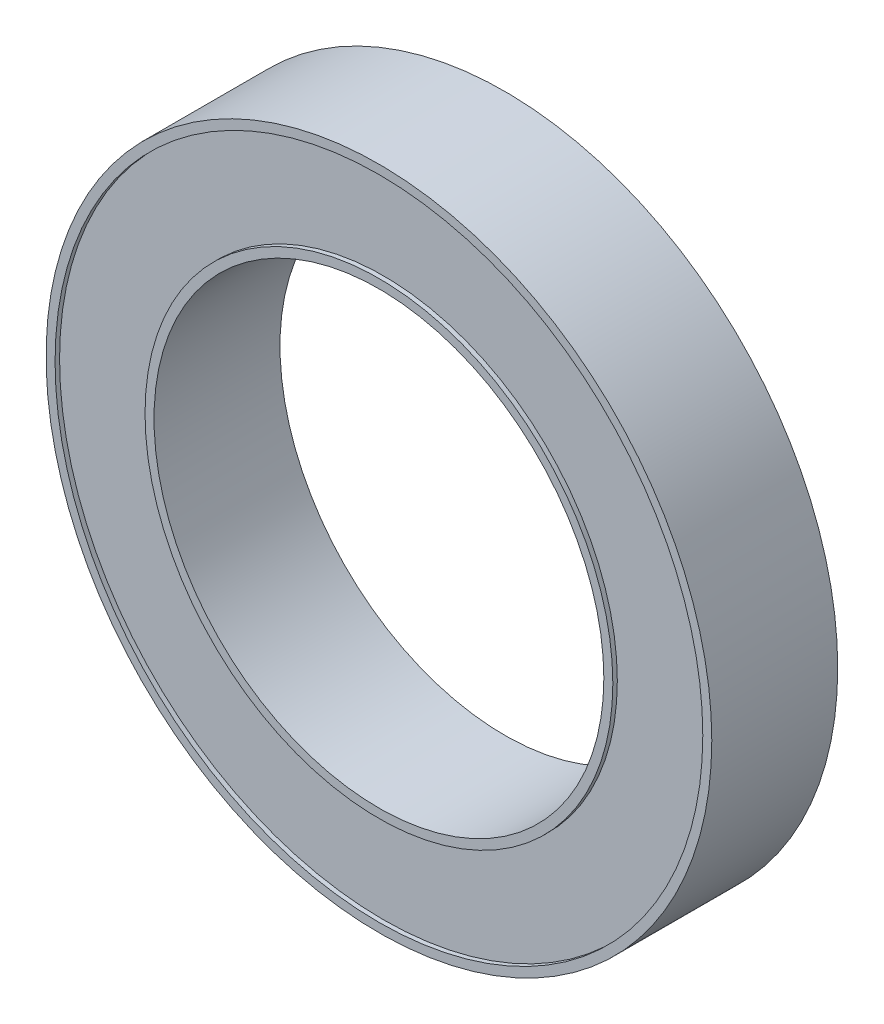
SolidWorks part; units mm, degrees
ref_plane "Front Plane" through (0, 0, 0) normal (0, 0, 1) x (1, 0, 0)
ref_plane "Top Plane" through (0, 0, 0) normal (0, 1, 0) x (1, 0, 0)
ref_plane "Right Plane" through (0, 0, 0) normal (1, 0, 0) x (0, 0, -1)
sketch "Sketch1" plane through (0, 0, 0) normal (0, 0, 1) x (1, 0, 0)
  circle A0 centre (0, 0) radius 12.5
  circle A1 centre (0, 0) radius 18.5
  dimension "D1" = 37
  dimension "D2" = 25
extrude "Boss-Extrude1" add sketch "Sketch1" along normal mid plane 7
sketch "Sketch2" plane through (0, 0, 3.5) normal (0, 0, 1) x (1, 0, 0)
  circle A2 centre (0, 0) radius 18
  circle A3 centre (0, 0) radius 18
  circle A5 centre (0, 0) radius 13
  circle A6 centre (0, 0) radius 13
  dimension "D1" = 0.5
  dimension "D2" = 0.5
extrude "Cut-Extrude1" cut sketch "Sketch2" against normal blind 0.25 contours A3 | A6
mirror "Mirror1" about plane through (0, 0, 0) normal (0, 0, 1) of "Cut-Extrude1"
equation "\"Bearing Internal 'd'\"= 25mm"
equation "\"Bearing External 'd'\"= 37mm"
equation "\"Bearing Width\"= 7mm"
equation "\"D1@Sketch1\"=\"Bearing External 'd'\"'''''''''"
equation "\"D2@Sketch1\"=\"Bearing Internal 'd'\"'''''''''"
equation "\"D1@Boss-Extrude1\"=\"Bearing Width\""
